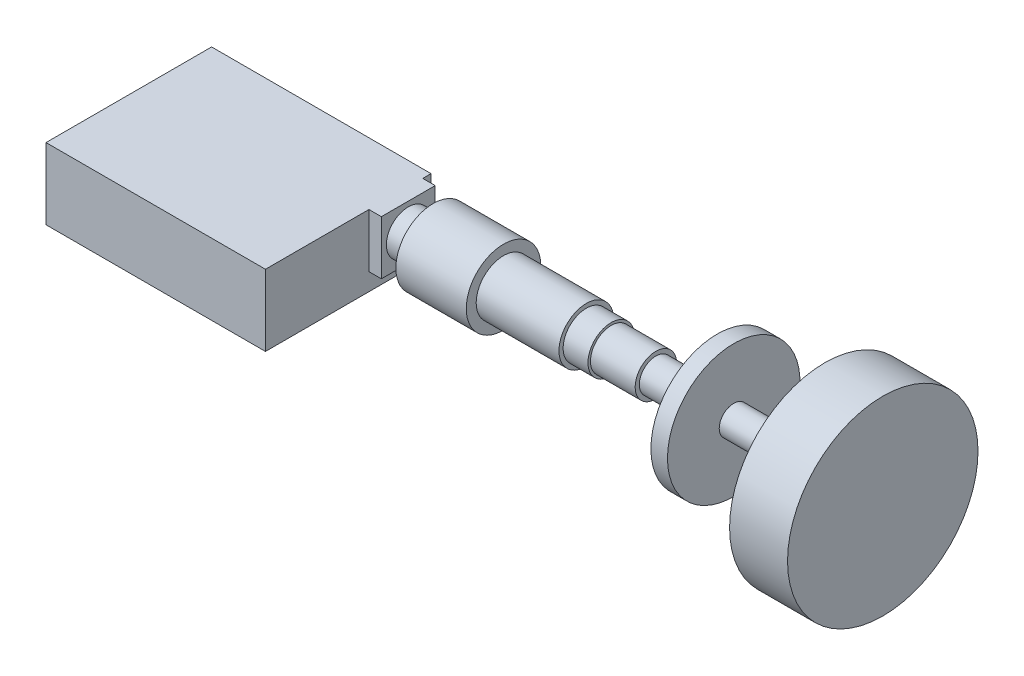
SolidWorks part; units mm, degrees
ref_plane "Front Plane" through (0, 0, 0) normal (0, 0, 1) x (1, 0, 0)
ref_plane "Top Plane" through (0, 0, 0) normal (0, 1, 0) x (1, 0, 0)
ref_plane "Right Plane" through (0, 0, 0) normal (1, 0, 0) x (0, 0, -1)
sketch "Sketch1" plane through (0, 0, 0) normal (0, 1, 0) x (1, 0, 0)
  line L1 (-13.25, -10) -> (13.25, -10)
  line L2 (-13.25, -10) -> (-13.25, 10)
  line L3 (-13.25, 10) -> (13.25, 10)
  line L4 (13.25, -10) -> (13.25, 10)
  line L5 (0, 10) -> (0, -10) construction
  line L6 (-13.25, 0) -> (13.25, 0) construction
  point P0 (0, 0)
  dimension "D1" = 20
  dimension "D2" = 26.5
extrude "Boss-Extrude1" add sketch "Sketch1" along normal blind 8.6
sketch "Sketch2" plane through (13.25, 0, 0) normal (1, 0, 0) x (0, 0, -1)
  line L0 (2.5, 8.6) -> (9, 8.6)
  line L1 (2.5, 8.6) -> (2.5, 2.1)
  line L2 (9, 8.6) -> (9, 2.1)
  line L3 (2.5, 2.1) -> (9, 2.1)
  line L4 (-10, 8.6) -> (10, 8.6) construction
  line L5 (10, 8.6) -> (10, 0) construction
  dimension "D1" = 6.5
  dimension "D2" = 1
extrude "Boss-Extrude2" add sketch "Sketch2" along normal blind 1.5
sketch "Sketch3" plane through (14.75, 0, 0) normal (1, 0, 0) x (0, 0, -1)
  line L0 (5.75, 8.6) -> (5.75, 2.1) construction
  line L1 (9, 8.6) -> (2.5, 8.6) construction
  line L2 (2.5, 2.1) -> (9, 2.1) construction
  circle A0 centre (5.75, 5.35) radius 2.65
  dimension "D1" = 5.3
ref_plane "Plane1" through (0, 0, -5.75) normal (0, 0, 1) x (1, 0, 0)
sketch "Sketch6" plane through (0, 0, -5.75) normal (0, 0, 1) x (1, 0, 0)
  line L0 (14.75, 5.35) -> (60.5073, 5.35) construction
  line L1 (14.75, 2.7) -> (14.75, 8) construction
  line L2 (14.75, 5.35) -> (14.75, 2.7)
  line L3 (14.75, 2.7) -> (17.75, 2.7)
  line L4 (17.75, 2.7) -> (17.75, 0.85)
  line L5 (17.75, 0.85) -> (26.25, 0.85)
  line L6 (26.25, 0.85) -> (26.25, 2.05)
  line L7 (26.25, 2.05) -> (36.25, 2.05)
  line L8 (36.25, 2.05) -> (36.25, 2.55)
  line L9 (36.25, 2.55) -> (39.25, 2.55)
  line L10 (39.25, 2.55) -> (39.25, 2.85)
  line L11 (39.25, 2.85) -> (44.65, 2.85)
  line L12 (44.65, 2.85) -> (44.65, 3.35)
  line L13 (44.65, 3.35) -> (52.05, 3.35)
  line L14 (52.05, 3.35) -> (52.05, -2.65)
  line L15 (52.05, -2.65) -> (54.05, -2.65)
  line L16 (54.05, -2.65) -> (54.05, 3.6)
  line L17 (54.05, 3.6) -> (65.05, 3.6)
  line L18 (65.05, 3.6) -> (65.05, -6.15)
  line L19 (65.05, -6.15) -> (72.05, -6.15)
  line L20 (72.05, -6.15) -> (72.05, 5.35)
  line L21 (72.05, 5.35) -> (14.75, 5.35)
  point P4 (16.25, 2.7)
  dimension "D1" = 2.65
  dimension "D2" = 3
  dimension "D3" = 4.5
  dimension "D4" = 8.5
  dimension "D5" = 3.3
  dimension "D6" = 10
  dimension "D7" = 2.8
  dimension "D8" = 3
  dimension "D9" = 2.5
  dimension "D10" = 5.4
  dimension "D11" = 2
  dimension "D12" = 7.4
  dimension "D13" = 2
  dimension "D14" = 8
  dimension "D15" = 1.75
  dimension "D16" = 7
  dimension "D17" = 11.5
  dimension "D18" = 11
revolve "Revolve1" add sketch "Sketch6" angle 360 about L0
